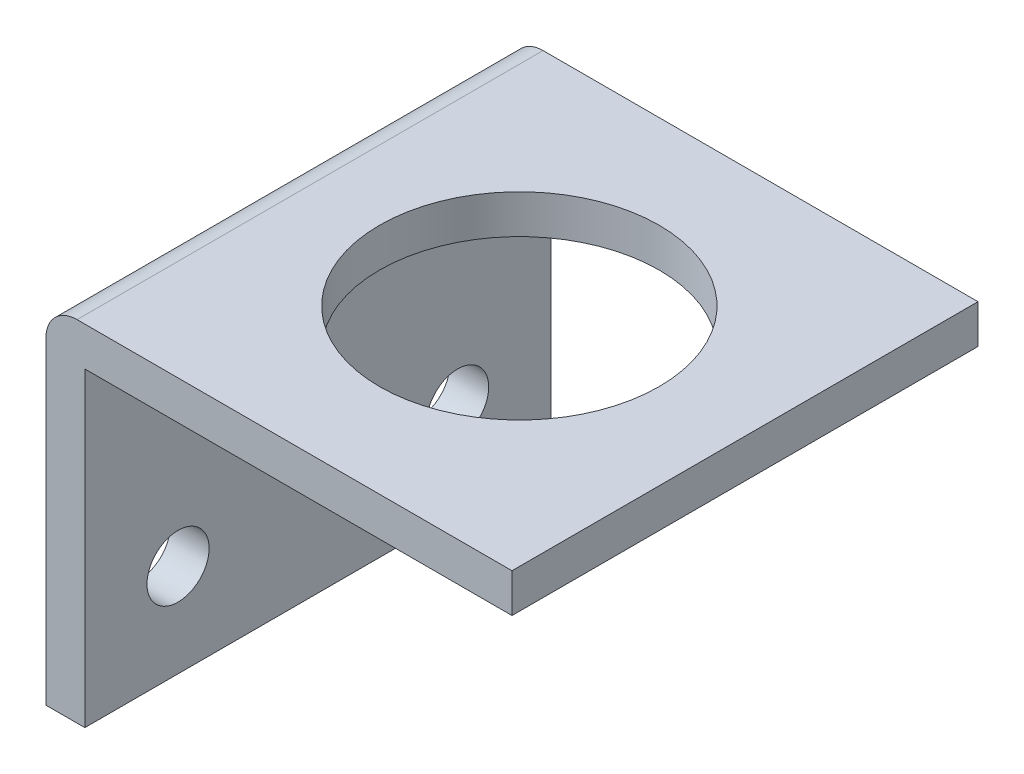
SolidWorks part; units mm, degrees
ref_plane "Front" through (0, 0, 0) normal (0, 0, 1) x (1, 0, 0)
ref_plane "Top" through (0, 0, 0) normal (0, 1, 0) x (1, 0, 0)
ref_plane "Right" through (0, 0, 0) normal (1, 0, 0) x (0, 0, -1)
sketch "Sketch1" plane through (0, 0, 0) normal (0, 0, 1) x (1, 0, 0)
  line L1 (0, 0) -> (3.175, 0)
  line L2 (0, 0) -> (0, 25.4)
  line L3 (0, 25.4) -> (3.175, 25.4)
  line L4 (3.175, 0) -> (3.175, 25.4)
  line L5 (0, 25.4) -> (38.1, 25.4)
  line L6 (0, 25.4) -> (0, 28.575)
  line L7 (0, 28.575) -> (38.1, 28.575)
  line L8 (38.1, 25.4) -> (38.1, 28.575)
  dimension "D1" = 25.4
  dimension "D2" = 3.175
  dimension "D3" = 3.175
  dimension "D4" = 38.1
extrude "Boss-Extrude1" add sketch "Sketch1" along normal blind 38.1 contours L5 L8 L7 L6 L3 | L1 L4 L3 L2
fillet "Fillet1" radius 2.54 1 edges at (0, 28.575, 19.05)
sketch "Sketch2" plane through (0, 28.575, 0) normal (0, 1, 0) x (1, 0, 0)
  line L0 (2.54, 0) -> (38.1, 0) construction
  circle A0 centre (19.6499, -19.05) radius 11.43
  dimension "D1" = 19.05
extrude "Cut-Extrude1" cut sketch "Sketch2" against normal blind 38.1
sketch "Sketch3" plane through (0, 0, 0) normal (-1, 0, 0) x (0, 0, 1)
  line L0 (0, 7.62) -> (38.1, 7.62) construction
  line L1 (0, 0) -> (0, 26.035) construction
  line L2 (38.1, 0) -> (38.1, 26.035) construction
  line L3 (38.1, 0) -> (0, 0) construction
  circle A0 centre (7.62, 7.62) radius 2.54
  circle A1 centre (30.48, 7.62) radius 2.54
  point P10 (0, 0)
  point P11 (0, 0)
  point P12 (0, 0)
  dimension "D1" = 5.08
  dimension "D2" = 7.62
  dimension "D3" = 7.62
  dimension "D4" = 7.62
extrude "Cut-Extrude3" cut sketch "Sketch3" against normal through all
